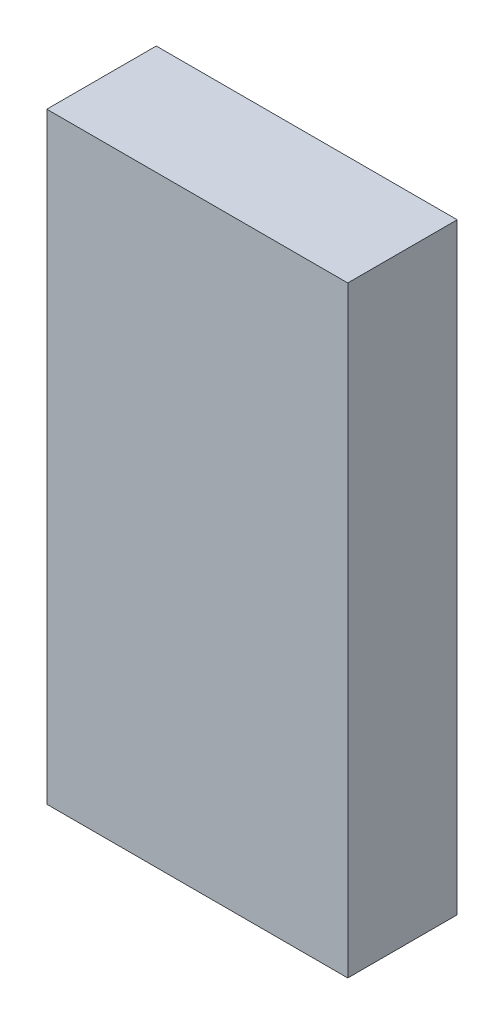
SolidWorks part; units mm, degrees
ref_plane "正面" through (0, 0, 0) normal (0, 0, 1) x (1, 0, 0)
ref_plane "平面" through (0, 0, 0) normal (0, 1, 0) x (1, 0, 0)
ref_plane "右側面" through (0, 0, 0) normal (1, 0, 0) x (0, 0, -1)
sketch "ｽｹｯﾁ1" plane through (0, 0, 0) normal (0, 0, 1) x (1, 0, 0)
  line L1 (0, 0) -> (110, 0)
  line L2 (0, 0) -> (0, 220)
  line L3 (0, 220) -> (110, 220)
  line L4 (110, 0) -> (110, 220)
  dimension "D1" = 110
  dimension "D2" = 220
extrude "ﾎﾞｽ - 押し出し1" add sketch "ｽｹｯﾁ1" along normal blind 40
